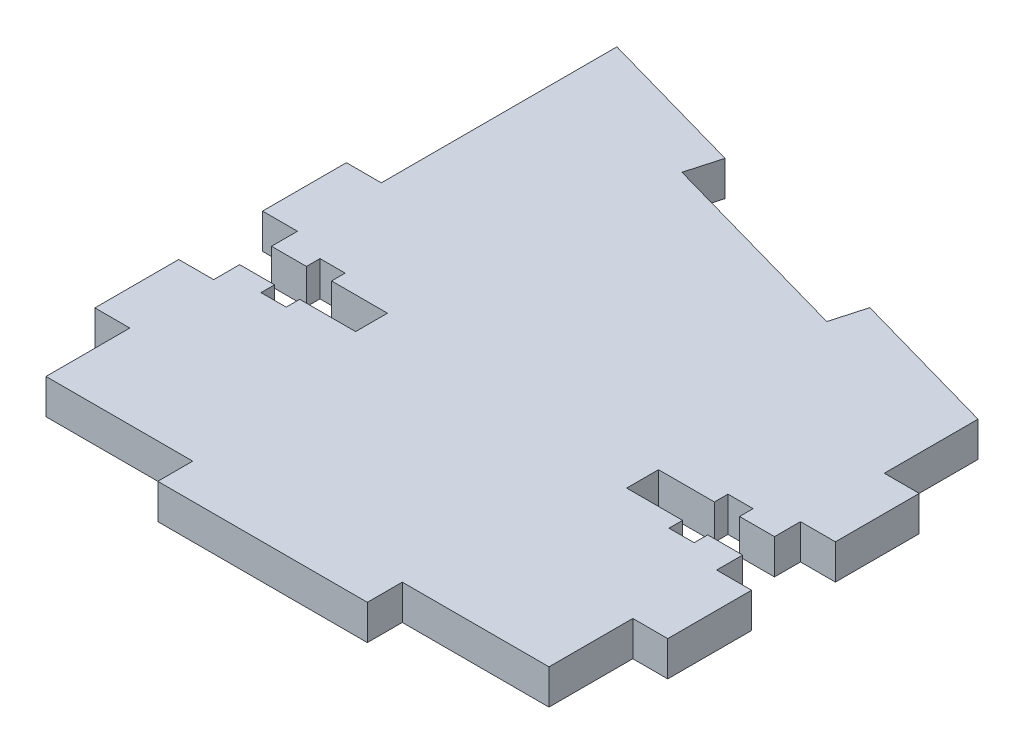
SolidWorks part; units mm, degrees
ref_plane "Front Plane" through (0, 0, 0) normal (0, 0, 1) x (1, 0, 0)
ref_plane "Top Plane" through (0, 0, 0) normal (0, 1, 0) x (1, 0, 0)
ref_plane "Right Plane" through (0, 0, 0) normal (1, 0, 0) x (0, 0, -1)
sketch "Sketch1" plane through (0, 0, 0) normal (0, 1, 0) x (1, 0, 0)
  line L0 (0, 0) -> (13.335, 0)
  line L1 (13.335, 0) -> (13.335, -3.175)
  line L2 (13.335, -3.175) -> (32.385, -3.175)
  line L3 (32.385, -3.175) -> (32.385, 0)
  line L4 (32.385, 0) -> (45.72, 0)
  line L5 (45.72, 0) -> (45.72, 7.62)
  line L6 (45.72, 7.62) -> (48.895, 7.62)
  line L7 (48.895, 7.62) -> (48.895, 15.24)
  line L8 (48.895, 15.24) -> (45.72, 15.24)
  line L9 (45.72, 15.24) -> (45.72, 22.86)
  line L10 (45.72, 22.86) -> (48.895, 22.86)
  line L11 (48.895, 22.86) -> (48.895, 30.48)
  line L12 (48.895, 30.48) -> (45.72, 30.48)
  line L13 (45.72, 30.48) -> (45.72, 38.9966)
  line L14 (45.72, 38.9966) -> (32.0273, 42.8587)
  line L15 (32.0273, 42.8587) -> (31.1654, 39.8029)
  line L16 (31.1654, 39.8029) -> (12.8308, 44.9743)
  line L17 (12.8308, 44.9743) -> (13.6927, 48.0301)
  line L18 (13.6927, 48.0301) -> (0, 51.8922)
  line L19 (0, 51.8922) -> (0, 30.48)
  line L20 (0, 30.48) -> (-3.175, 30.48)
  line L21 (-3.175, 30.48) -> (-3.175, 22.86)
  line L22 (-3.175, 22.86) -> (0, 22.86)
  line L23 (0, 22.86) -> (0, 15.24)
  line L24 (0, 15.24) -> (-3.175, 15.24)
  line L25 (-3.175, 15.24) -> (-3.175, 7.62)
  line L26 (-3.175, 7.62) -> (0, 7.62)
  line L27 (0, 7.62) -> (0, 0)
  dimension "D1" = 3.175
  dimension "D2" = 45.72
  dimension "D3" = 19.05
  dimension "D4" = 19.05
  dimension "D5" = 38.9966
  dimension "D6" = 51.8922
  dimension "D7" = 7.62
  dimension "D8" = 7.62
extrude "Boss-Extrude1" add sketch "Sketch1" along normal blind 3.175
sketch "Sketch2" plane through (0, 3.175, 0) normal (0, 1, 0) x (1, 0, 0)
  line L0 (0, 20.4978) -> (3.175, 20.4978)
  line L1 (0, 22.86) -> (0, 15.24) construction
  line L2 (3.175, 20.4978) -> (3.175, 21.7297)
  line L3 (3.175, 21.7297) -> (5.461, 21.7297)
  line L4 (5.461, 21.7297) -> (5.461, 20.4978)
  line L5 (5.461, 20.4978) -> (10.541, 20.4978)
  line L6 (10.541, 20.4978) -> (10.541, 17.6022)
  line L7 (10.541, 17.6022) -> (5.461, 17.6022)
  line L8 (5.461, 17.6022) -> (5.461, 16.3703)
  line L9 (5.461, 16.3703) -> (3.175, 16.3703)
  line L10 (3.175, 16.3703) -> (3.175, 17.6022)
  line L11 (3.175, 17.6022) -> (0, 17.6022)
  line L12 (10.541, 19.05) -> (0, 19.05) construction
  line L13 (22.86, -3.175) -> (22.86, 40.61) construction
  line L14 (13.335, -3.175) -> (32.385, -3.175) construction
  line L15 (42.545, 17.6022) -> (45.72, 17.6022)
  line L16 (42.545, 16.3703) -> (42.545, 17.6022)
  line L17 (40.259, 16.3703) -> (42.545, 16.3703)
  line L18 (40.259, 17.6022) -> (40.259, 16.3703)
  line L19 (35.179, 17.6022) -> (40.259, 17.6022)
  line L20 (35.179, 20.4978) -> (35.179, 17.6022)
  line L21 (40.259, 20.4978) -> (35.179, 20.4978)
  line L22 (40.259, 21.7297) -> (40.259, 20.4978)
  line L23 (42.545, 21.7297) -> (40.259, 21.7297)
  line L24 (42.545, 20.4978) -> (42.545, 21.7297)
  line L25 (45.72, 20.4978) -> (42.545, 20.4978)
  line L26 (0, 20.4978) -> (0, 17.6022)
  line L27 (45.72, 20.4978) -> (45.72, 17.6022)
  dimension "D1" = 2.8956
  dimension "D2" = 3.175
  dimension "D3" = 5.08
  dimension "D4" = 2.286
  dimension "D5" = 5.3594
extrude "Cut-Extrude1" cut sketch "Sketch2" against normal through all
